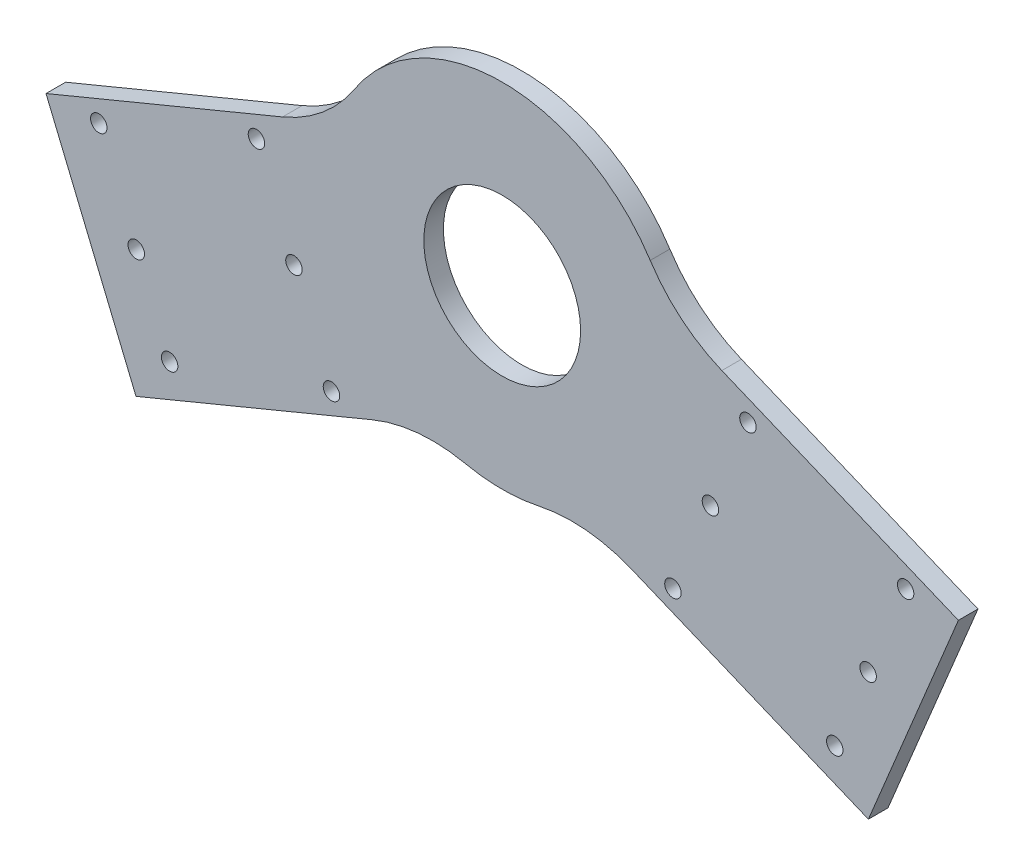
SolidWorks part; units mm, degrees
ref_plane "Front Plane" through (0, 0, 0) normal (0, 0, 1) x (1, 0, 0)
ref_plane "Top Plane" through (0, 0, 0) normal (0, 1, 0) x (1, 0, 0)
ref_plane "Right Plane" through (0, 0, 0) normal (1, 0, 0) x (0, 0, -1)
sketch "Sketch1" plane through (0, 0, 0) normal (0, 0, 1) x (1, 0, 0)
  line L0 (0, 0) -> (0, 50000) construction
  line L1 (0, 0) -> (50000, 0) construction
  line L2 (0, 0) -> (-935.0114, -387.2944) construction
  line L3 (0, 0) -> (18.1262, -8.4524) construction
  line L5 (-93.4177, -71.1667) -> (-116.3787, -15.7339)
  line L7 (-116.3787, -15.7339) -> (-42.4684, 14.8808)
  line L16 (0, 0) -> (935.0114, -387.2944) construction
  line L17 (116.3787, -15.7339) -> (42.4684, 14.8808)
  line L18 (-93.4177, -71.1667) -> (-19.5074, -40.552)
  line L19 (93.4177, -71.1667) -> (19.5074, -40.552)
  line L20 (93.4177, -71.1667) -> (116.3787, -15.7339)
  line L21 (-104.8302, -10.9503) -> (-81.8692, -66.3831) construction
  line L22 (-64.6045, 5.7117) -> (-41.6435, -49.7211) construction
  circle A2 centre (0, 0) radius 20
  arc A4 (42.4684, 14.8808) -> (-42.4684, 14.8808) centre (0, 0) ccw
  arc A6 (19.5074, -40.552) -> (-19.5074, -40.552) centre (0, 0) cw
  circle A7 centre (-93.3497, -38.6667) radius 2.1
  circle A8 centre (-102.9168, -15.5697) radius 2.1
  circle A9 centre (-84.8388, -59.214) radius 2.1
  circle A10 centre (84.8388, -59.214) radius 2.1
  circle A11 centre (93.3497, -38.6667) radius 2.1
  circle A12 centre (102.9168, -15.5697) radius 2.1
  circle A13 centre (-62.6911, 1.0923) radius 2.1
  circle A14 centre (-53.124, -22.0047) radius 2.1
  circle A15 centre (-43.5569, -45.1017) radius 2.1
  circle A16 centre (43.5569, -45.1017) radius 2.1
  circle A17 centre (53.124, -22.0047) radius 2.1
  circle A18 centre (62.6911, 1.0923) radius 2.1
  point P12 (-104.8982, -43.4503)
  dimension "D2" = 30
  dimension "D6" = 40
  dimension "D4" = 45
  dimension "D7" = 4.2
  dimension "D1" = 67.5
  dimension "D3" = 12.5
  dimension "D5" = 80
  dimension "D8" = 5
  dimension "D9" = 43.54
  dimension "D10" = 5
  dimension "D11" = 5
extrude "Boss-Extrude1" add sketch "Sketch1" along normal blind 5
fillet "Fillet1" radius 40 4 edges at (-42.4684, 14.8808, 2.5) (42.4684, 14.8808, 2.5) (19.5074, -40.552, 2.5) (-19.5074, -40.552, 2.5)
